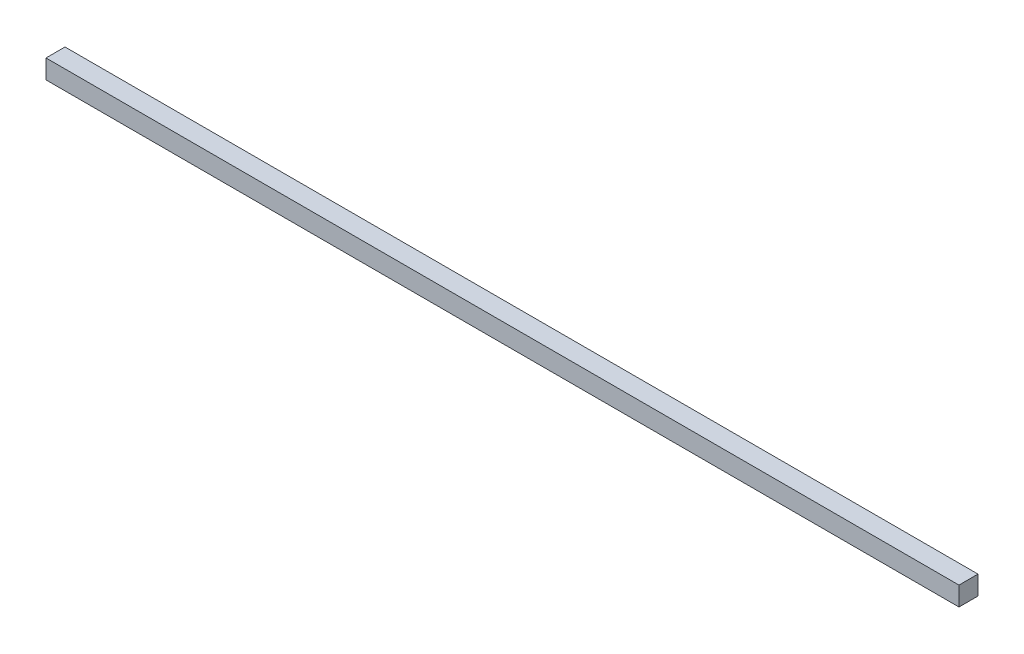
SolidWorks part; units mm, degrees
ref_plane "Front Plane" through (0, 0, 0) normal (0, 0, 1) x (1, 0, 0)
ref_plane "Top Plane" through (0, 0, 0) normal (0, 1, 0) x (1, 0, 0)
ref_plane "Right Plane" through (0, 0, 0) normal (1, 0, 0) x (0, 0, -1)
sketch "Sketch1" plane through (0, 0, 0) normal (1, 0, 0) x (0, 0, -1)
  line L1 (-3.175, 3.175) -> (3.175, 3.175)
  line L2 (-3.175, 3.175) -> (-3.175, -3.175)
  line L3 (-3.175, -3.175) -> (3.175, -3.175)
  line L4 (3.175, 3.175) -> (3.175, -3.175)
  line L5 (-3.175, 3.175) -> (3.175, -3.175) construction
  line L6 (-3.175, -3.175) -> (3.175, 3.175) construction
  point P0 (0, 0)
  dimension "D1" = 6.35
  dimension "D2" = 6.35
extrude "Boss-Extrude1" add sketch "Sketch1" along normal mid plane 304.8
